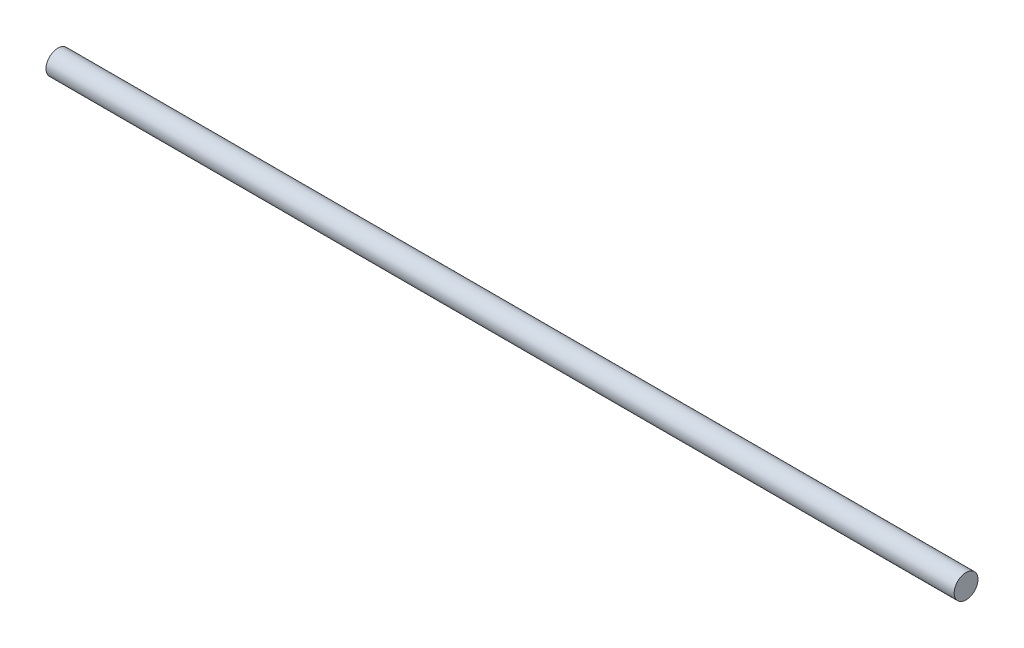
SolidWorks part; units mm, degrees
ref_plane "Front Plane" through (0, 0, 0) normal (0, 0, 1) x (1, 0, 0)
ref_plane "Top Plane" through (0, 0, 0) normal (0, 1, 0) x (1, 0, 0)
ref_plane "Right Plane" through (0, 0, 0) normal (1, 0, 0) x (0, 0, -1)
sketch "Sketch1" plane through (0, 0, 0) normal (1, 0, 0) x (0, 0, -1)
  circle A0 centre (0, 0) radius 4
  dimension "D1" = 8
extrude "Boss-Extrude1" add sketch "Sketch1" along normal blind 305
